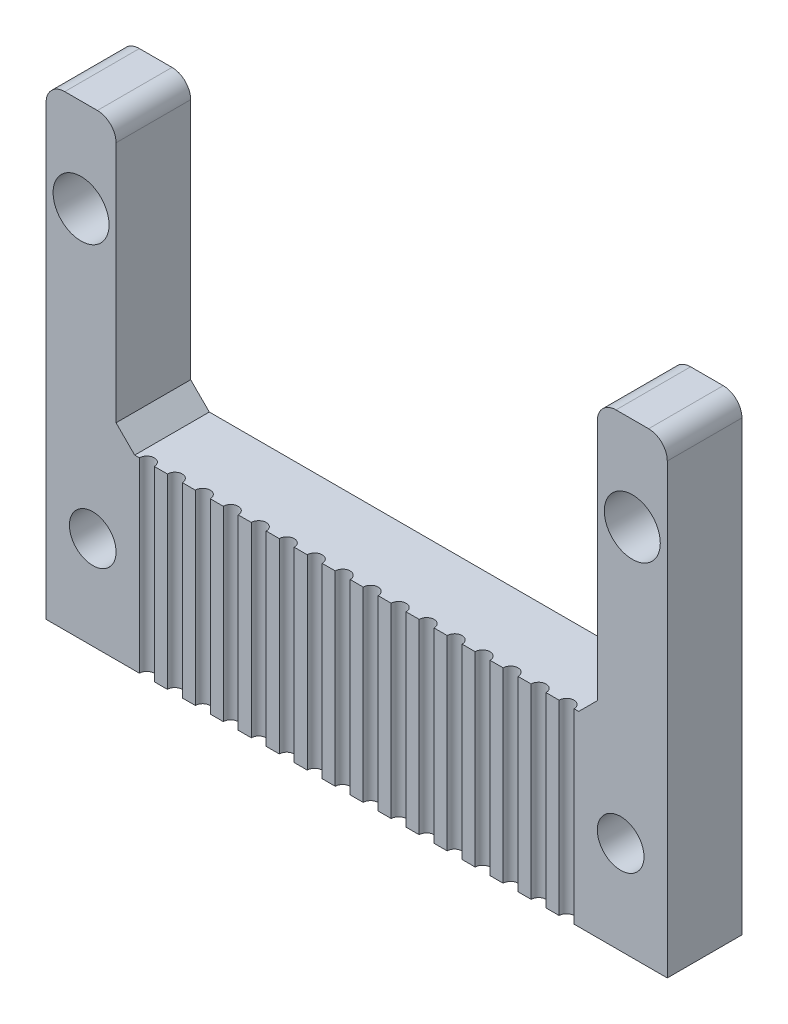
SolidWorks part; units mm, degrees
ref_plane "前视基准面" through (0, 0, 0) normal (0, 0, 1) x (1, 0, 0)
ref_plane "上视基准面" through (0, 0, 0) normal (0, 1, 0) x (1, 0, 0)
ref_plane "右视基准面" through (0, 0, 0) normal (1, 0, 0) x (0, 0, -1)
other "Configuration Table"
sketch "草图1" plane through (0, 0, 0) normal (0, 1, 0) x (1, 0, 0)
  line L0 (-10.8, 0) -> (-0.8, 0)
  line L1 (-10.8, 0) -> (-10.8, 8)
  line L2 (-10.8, 8) -> (55.8, 8)
  line L3 (55.8, 8) -> (55.8, 0)
  line L4 (0.8, 0) -> (2.2, 0)
  line L5 (3.8, 0) -> (5.2, 0)
  line L6 (6.8, 0) -> (8.2, 0)
  line L7 (9.8, 0) -> (11.2, 0)
  line L8 (12.8, 0) -> (14.2, 0)
  line L9 (15.8, 0) -> (17.2, 0)
  line L10 (18.8, 0) -> (20.2, 0)
  line L11 (21.8, 0) -> (23.2, 0)
  line L12 (24.8, 0) -> (26.2, 0)
  line L13 (27.8, 0) -> (29.2, 0)
  line L14 (30.8, 0) -> (32.2, 0)
  line L15 (33.8, 0) -> (35.2, 0)
  line L16 (36.8, 0) -> (38.2, 0)
  line L17 (39.8, 0) -> (41.2, 0)
  line L18 (42.8, 0) -> (44.2, 0)
  line L19 (45.8, 0) -> (55.8, 0)
  arc A0 (0.8, 0) -> (-0.8, 0) centre (0, 0) ccw
  arc A1 (3.8, 0) -> (2.2, 0) centre (3, 0) ccw
  arc A2 (6.8, 0) -> (5.2, 0) centre (6, 0) ccw
  arc A3 (9.8, 0) -> (8.2, 0) centre (9, 0) ccw
  arc A4 (12.8, 0) -> (11.2, 0) centre (12, 0) ccw
  arc A5 (15.8, 0) -> (14.2, 0) centre (15, 0) ccw
  arc A6 (18.8, 0) -> (17.2, 0) centre (18, 0) ccw
  arc A7 (21.8, 0) -> (20.2, 0) centre (21, 0) ccw
  arc A8 (24.8, 0) -> (23.2, 0) centre (24, 0) ccw
  arc A9 (27.8, 0) -> (26.2, 0) centre (27, 0) ccw
  arc A10 (30.8, 0) -> (29.2, 0) centre (30, 0) ccw
  arc A11 (33.8, 0) -> (32.2, 0) centre (33, 0) ccw
  arc A12 (36.8, 0) -> (35.2, 0) centre (36, 0) ccw
  arc A13 (39.8, 0) -> (38.2, 0) centre (39, 0) ccw
  arc A14 (42.8, 0) -> (41.2, 0) centre (42, 0) ccw
  arc A15 (45.8, 0) -> (44.2, 0) centre (45, 0) ccw
  dimension "D1" = 1.6
  dimension "D4" = 10
  dimension "D5" = 8
  dimension "D3" = 66.6
  dimension "D2" = 16
extrude "凸台-拉伸1" add sketch "草图1" along normal blind 20
sketch "草图3" plane through (0, 0, 0) normal (0, 0, 1) x (1, 0, 0)
  line L0 (-10.8, 10) -> (-5.8, 10) construction
  line L1 (-10.8, 20) -> (-10.8, 0) construction
  line L2 (55.8, 10) -> (50.8, 10) construction
  line L3 (55.8, 20) -> (55.8, 0) construction
  circle A0 centre (50.8, 10) radius 2.5
  circle A1 centre (-5.8, 10) radius 2.5
  dimension "D1" = 5
  dimension "D4" = 5
  dimension "D2" = 5
  dimension "D3" = 5
extrude "切除-拉伸1" cut sketch "草图3" against normal blind 4
sketch "草图4" plane through (0, 0, -4) normal (0, 0, 1) x (1, 0, 0)
  circle A0 centre (-5.8, 10) radius 1.5
  circle A1 centre (50.8, 10) radius 1.5
  dimension "D1" = 3
  dimension "D2" = 3
extrude "切除-拉伸2" cut sketch "草图4" against normal blind 14
sketch "草图5" plane through (0, 20, 0) normal (0, 1, 0) x (1, 0, 0)
  line L0 (45.8, 0) -> (55.8, 0) construction
  line L1 (-10.8, 8) -> (-3.3, 8)
  line L2 (-10.8, 8) -> (-10.8, 0)
  line L3 (-10.8, 0) -> (-3.3, 0)
  line L4 (-3.3, 8) -> (-3.3, 0)
  line L5 (55.8, 8) -> (48.3, 8)
  line L6 (55.8, 8) -> (55.8, 0)
  line L7 (55.8, 0) -> (48.3, 0)
  line L8 (48.3, 8) -> (48.3, 0)
  dimension "D1" = 7.5
extrude "凸台-拉伸2" add sketch "草图5" along normal blind 30
sketch "草图6" plane through (0, 0, 0) normal (0, 0, 1) x (1, 0, 0)
  line L0 (-10.8, 50) -> (-3.3, 50) construction
  line L1 (-10.8, 50) -> (-10.8, 0) construction
  line L2 (48.3, 50) -> (55.8, 50) construction
  line L3 (48.3, 50) -> (48.3, 20) construction
  circle A0 centre (-7.05, 40) radius 3
  circle A1 centre (52.05, 40) radius 3
  dimension "D1" = 6
  dimension "D3" = 3.75
  dimension "D4" = 6
  dimension "D5" = 10
  dimension "D6" = 3.75
  dimension "D2" = 10
extrude "切除-拉伸3" cut sketch "草图6" against normal blind 6
sketch "草图7" plane through (0, 0, -6) normal (0, 0, 1) x (1, 0, 0)
  circle A0 centre (-7.05, 40) radius 1.5
  circle A1 centre (52.05, 40) radius 1.5
  dimension "D1" = 3
  dimension "D2" = 3
extrude "切除-拉伸4" cut sketch "草图7" against normal blind 6
chamfer "倒角1" distance 2 angle 45 2 edges at (-3.3, 20, -4) (48.3, 20, -4)
fillet "圆角1" radius 2 4 edges at (55.8, 50, -4) (48.3, 50, -4) (-3.3, 50, -4) (-10.8, 50, -4)
